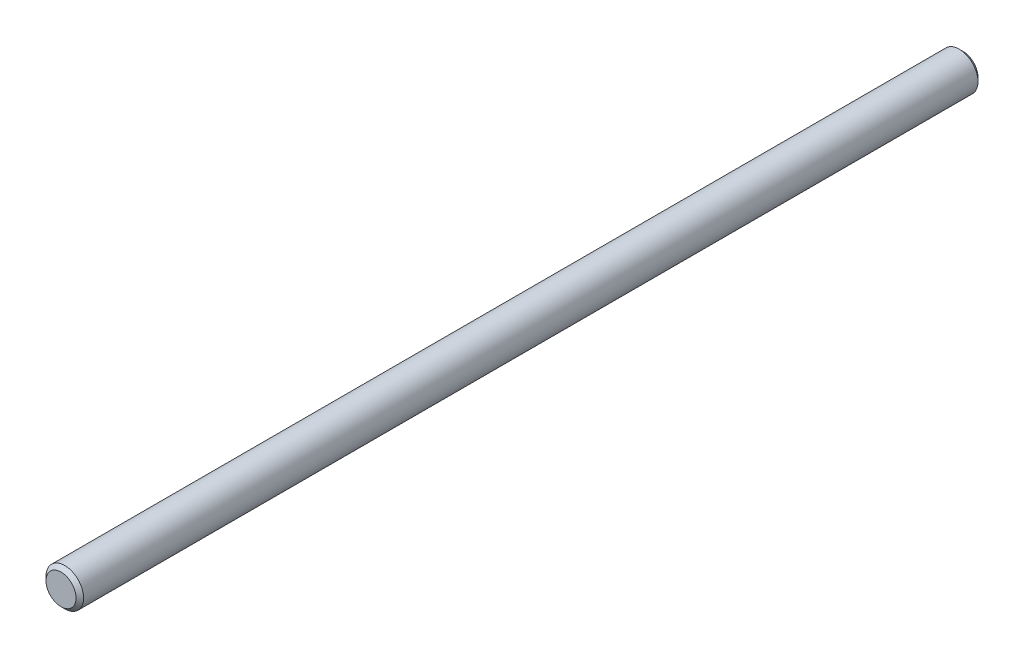
SolidWorks part; units mm, degrees
ref_plane "Front" through (0, 0, 0) normal (0, 0, 1) x (1, 0, 0)
ref_plane "Top" through (0, 0, 0) normal (0, 1, 0) x (1, 0, 0)
ref_plane "Right" through (0, 0, 0) normal (1, 0, 0) x (0, 0, -1)
sketch "Sketch1" plane through (0, 0, 0) normal (0, 0, 1) x (1, 0, 0)
  circle A0 centre (0, 0) radius 3.175
  dimension "D1" = 6.35
extrude "Extrude1" add sketch "Sketch1" along normal mid plane 152.4
chamfer "Chamfer1" distance 0.635 angle 45 2 edges at (3.175, 0, -76.2) (3.175, 0, 76.2)
equation "\"D1@Chamfer1\" = \"D1@Sketch1\" * .1"
